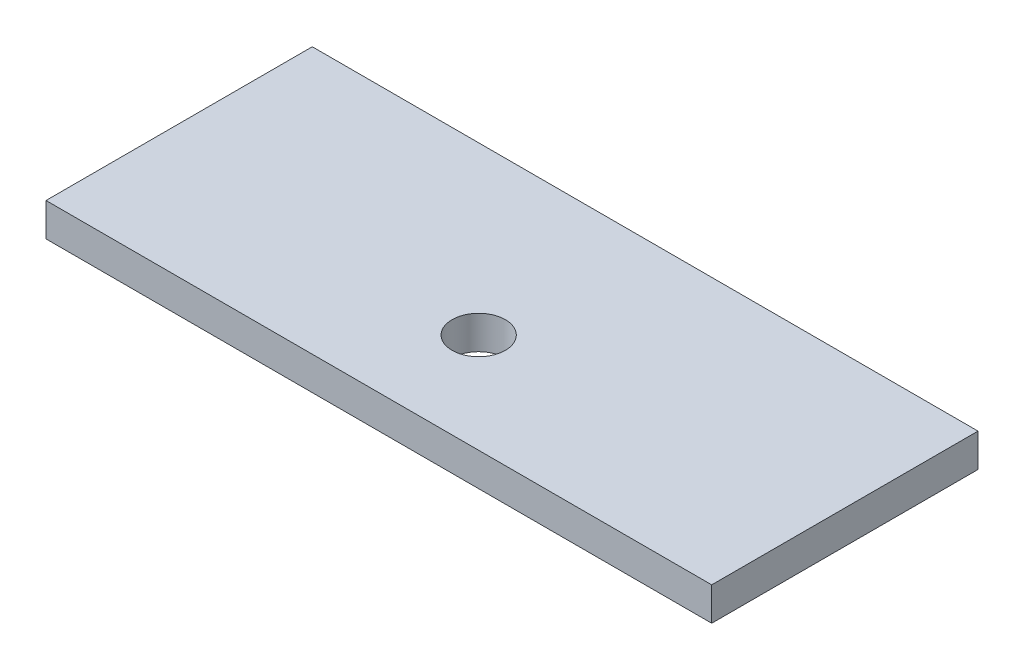
SolidWorks part; units mm, degrees
ref_plane "Alzado" through (0, 0, 0) normal (0, 0, 1) x (1, 0, 0)
ref_plane "Planta" through (0, 0, 0) normal (0, 1, 0) x (1, 0, 0)
ref_plane "Vista lateral" through (0, 0, 0) normal (1, 0, 0) x (0, 0, -1)
sketch "Croquis1" plane through (0, 0, 0) normal (0, 1, 0) x (1, 0, 0)
  line L0 (-50, 20) -> (50, -20) construction
  line L1 (-50, 20) -> (50, 20)
  line L2 (-50, 20) -> (-50, -20)
  line L3 (-50, -20) -> (50, -20)
  line L4 (50, 20) -> (50, -20)
  dimension "D1" = 100
  dimension "D2" = 40
extrude "Extruir1" add sketch "Croquis1" along normal blind 5
sketch "Croquis2" plane through (0, 5, 0) normal (0, 1, 0) x (1, 0, 0)
  line L0 (0, 20) -> (0, -20) construction
  line L1 (50, 20) -> (-50, 20) construction
  line L2 (-50, -20) -> (50, -20) construction
  circle A0 centre (0, -5) radius 4
  dimension "D1" = 8
  dimension "D2" = 15
extrude "Extruir2" cut sketch "Croquis2" against normal blind 5
